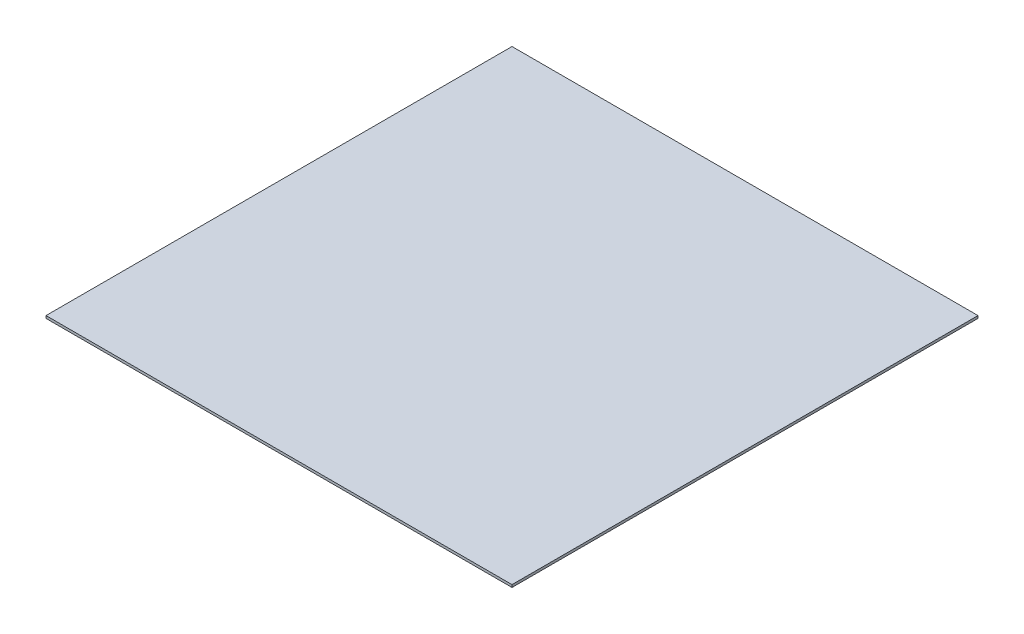
SolidWorks part; units mm, degrees
ref_plane "Front Plane" through (0, 0, 0) normal (0, 0, 1) x (1, 0, 0)
ref_plane "Top Plane" through (0, 0, 0) normal (0, 1, 0) x (1, 0, 0)
ref_plane "Right Plane" through (0, 0, 0) normal (1, 0, 0) x (0, 0, -1)
sketch "Sketch1" plane through (0, 0, 0) normal (0, 1, 0) x (1, 0, 0)
  line L1 (0, 0) -> (560, 0)
  line L2 (0, 0) -> (0, 560)
  line L3 (0, 560) -> (560, 560)
  line L4 (560, 0) -> (560, 560)
  dimension "D1" = 560
  dimension "D2" = 560
extrude "Boss-Extrude1" add sketch "Sketch1" along normal blind 3
